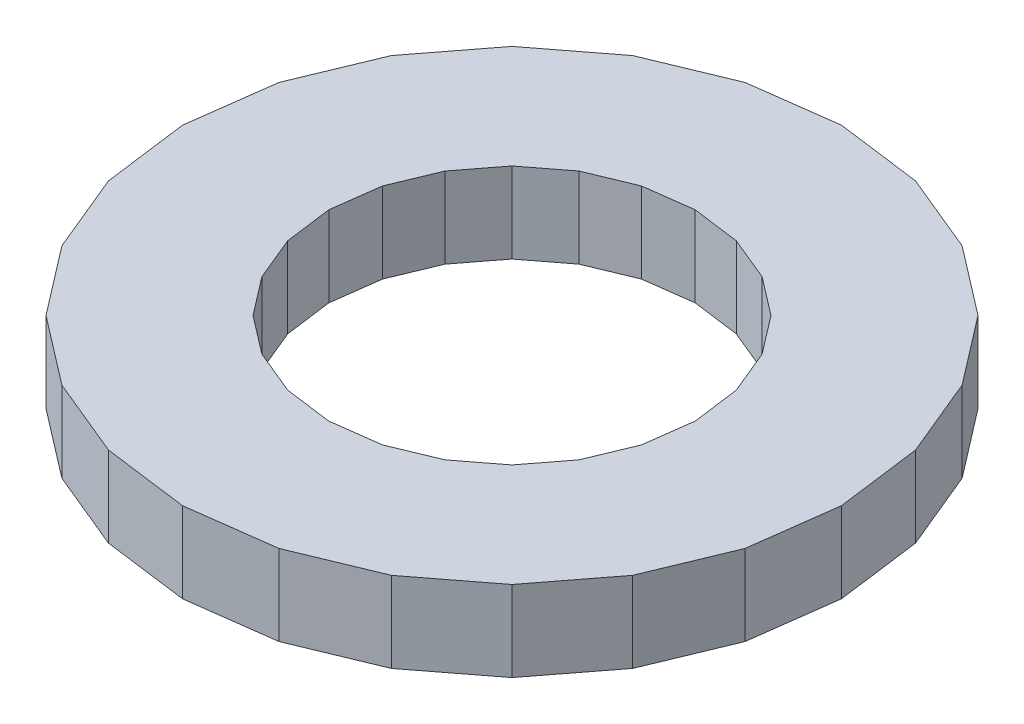
SolidWorks part; units mm, degrees
ref_plane "Front Plane" through (0, 0, 0) normal (0, 0, 1) x (1, 0, 0)
ref_plane "Top Plane" through (0, 0, 0) normal (0, 1, 0) x (1, 0, 0)
ref_plane "Right Plane" through (0, 0, 0) normal (1, 0, 0) x (0, 0, -1)
sketch "Sketch3" plane through (0, 0, 0) normal (0, 1, 0) x (1, 0, 0)
  line L0 (0, 0) -> (-43.2529, 0) construction
  line L1 (-77.8388, 0) -> (-75.1865, -20.1462)
  line L2 (-75.1865, -20.1462) -> (-67.4104, -38.9194)
  line L3 (-67.4104, -38.9194) -> (-55.0403, -55.0403)
  line L4 (-55.0403, -55.0403) -> (-38.9194, -67.4104)
  line L5 (-38.9194, -67.4104) -> (-20.1462, -75.1865)
  line L6 (-20.1462, -75.1865) -> (0, -77.8388)
  line L7 (0, -77.8388) -> (20.1462, -75.1865)
  line L8 (20.1462, -75.1865) -> (38.9194, -67.4104)
  line L9 (38.9194, -67.4104) -> (55.0403, -55.0403)
  line L10 (55.0403, -55.0403) -> (67.4104, -38.9194)
  line L11 (67.4104, -38.9194) -> (75.1865, -20.1462)
  line L12 (75.1865, -20.1462) -> (77.8388, 0)
  line L13 (77.8388, 0) -> (75.1865, 20.1462)
  line L14 (75.1865, 20.1462) -> (67.4104, 38.9194)
  line L15 (67.4104, 38.9194) -> (55.0403, 55.0403)
  line L16 (55.0403, 55.0403) -> (38.9194, 67.4104)
  line L17 (38.9194, 67.4104) -> (20.1462, 75.1865)
  line L18 (20.1462, 75.1865) -> (0, 77.8388)
  line L19 (0, 77.8388) -> (-20.1462, 75.1865)
  line L20 (-20.1462, 75.1865) -> (-38.9194, 67.4104)
  line L21 (-38.9194, 67.4104) -> (-55.0403, 55.0403)
  line L22 (-55.0403, 55.0403) -> (-67.4104, 38.9194)
  line L23 (-67.4104, 38.9194) -> (-75.1865, 20.1462)
  line L24 (-75.1865, 20.1462) -> (-77.8388, 0)
  line L25 (-43.2529, 0) -> (-41.7791, -11.1947)
  line L26 (-41.7791, -11.1947) -> (-37.4581, -21.6264)
  line L27 (-37.4581, -21.6264) -> (-30.5844, -30.5844)
  line L28 (-30.5844, -30.5844) -> (-21.6264, -37.4581)
  line L29 (-21.6264, -37.4581) -> (-11.1947, -41.7791)
  line L30 (-11.1947, -41.7791) -> (0, -43.2529)
  line L31 (0, -43.2529) -> (11.1947, -41.7791)
  line L32 (11.1947, -41.7791) -> (21.6264, -37.4581)
  line L33 (21.6264, -37.4581) -> (30.5844, -30.5844)
  line L34 (30.5844, -30.5844) -> (37.4581, -21.6264)
  line L35 (37.4581, -21.6264) -> (41.7791, -11.1947)
  line L36 (41.7791, -11.1947) -> (43.2529, 0)
  line L37 (43.2529, 0) -> (41.7791, 11.1947)
  line L38 (41.7791, 11.1947) -> (37.4581, 21.6264)
  line L39 (37.4581, 21.6264) -> (30.5844, 30.5844)
  line L40 (30.5844, 30.5844) -> (21.6264, 37.4581)
  line L41 (21.6264, 37.4581) -> (11.1947, 41.7791)
  line L42 (11.1947, 41.7791) -> (0, 43.2529)
  line L43 (0, 43.2529) -> (-11.1947, 41.7791)
  line L44 (-11.1947, 41.7791) -> (-21.6264, 37.4581)
  line L45 (-21.6264, 37.4581) -> (-30.5844, 30.5844)
  line L46 (-30.5844, 30.5844) -> (-37.4581, 21.6264)
  line L47 (-37.4581, 21.6264) -> (-41.7791, 11.1947)
  line L48 (-41.7791, 11.1947) -> (-43.2529, 0)
  line L49 (-77.8388, 0) -> (-43.2529, 0) construction
  circle A0 centre (0, 0) radius 77.1729 construction
  circle A1 centre (0, 0) radius 42.8829 construction
  dimension "D1" = 20.32
  dimension "D2" = 34.29
extrude "Boss-Extrude3" add sketch "Sketch3" along normal blind 19.05
